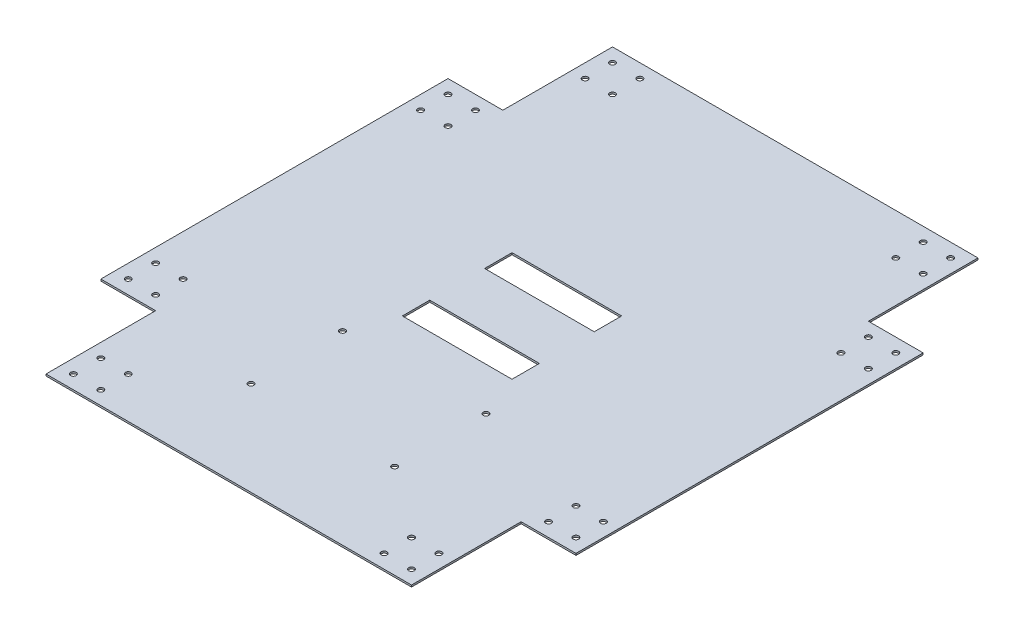
SolidWorks part; units mm, degrees
material "Thornel Mat VMA"
ref_plane "前视基准面" through (0, 0, 0) normal (0, 0, 1) x (1, 0, 0)
ref_plane "上视基准面" through (0, 0, 0) normal (0, 1, 0) x (1, 0, 0)
ref_plane "右视基准面" through (0, 0, 0) normal (1, 0, 0) x (0, 0, -1)
other "Configuration Table"
sketch "草图1" plane through (0, 0, 0) normal (0, 1, 0) x (1, 0, 0)
  line L0 (-154.7477, 33.3852) -> (-154.7477, 153.3852)
  line L1 (-154.7477, 153.3852) -> (245.2523, 153.3852)
  line L2 (245.2523, 153.3852) -> (245.2523, 33.3852)
  line L3 (245.2523, 33.3852) -> (305.2523, 33.3852)
  line L4 (305.2523, 33.3852) -> (305.2523, -346.6148)
  line L5 (305.2523, -346.6148) -> (245.2523, -346.6148)
  line L6 (245.2523, -346.6148) -> (245.2523, -466.6148)
  line L7 (245.2523, -466.6148) -> (-154.7477, -466.6148)
  line L8 (-154.7477, -466.6148) -> (-154.7477, -346.6148)
  line L9 (-154.7477, -346.6148) -> (-214.7477, -346.6148)
  line L10 (-214.7477, -346.6148) -> (-214.7477, 33.3852)
  line L11 (-214.7477, 33.3852) -> (-154.7477, 33.3852)
  line L12 (305.2523, -126.6148) -> (-214.7477, -126.6148)
  line L13 (-214.7477, -186.6148) -> (305.2523, -186.6148)
  line L14 (45.2523, -240.6148) -> (45.2523, -386.6148) construction
  line L15 (-38.2477, -240.6148) -> (128.7523, -240.6148)
  line L16 (-38.2477, -240.6148) -> (-38.2477, -386.6148)
  line L17 (-38.2477, -386.6148) -> (128.7523, -386.6148)
  line L18 (128.7523, -240.6148) -> (128.7523, -386.6148)
  line L19 (45.2523, 153.3852) -> (45.2523, -466.6148) construction
  line L20 (305.2523, -156.6148) -> (-214.7477, -156.6148) construction
  line L22 (-14.7477, -96.6148) -> (105.2523, -96.6148)
  line L23 (-14.7477, -96.6148) -> (-14.7477, -126.6148)
  line L25 (105.2523, -96.6148) -> (105.2523, -126.6148)
  line L30 (105.2523, -216.6148) -> (105.2523, -186.6148)
  line L31 (-14.7477, -216.6148) -> (105.2523, -216.6148)
  line L32 (-14.7477, -216.6148) -> (-14.7477, -186.6148)
  circle A0 centre (-33.2477, -263.6148) radius 3.1
  circle A1 centre (-33.2477, -363.6148) radius 3.1
  circle A2 centre (123.7523, -263.6148) radius 3.1
  circle A3 centre (123.7523, -363.6148) radius 3.1
  circle A4 centre (-139.7477, -421.6148) radius 3.1
  circle A5 centre (-109.7477, -421.6148) radius 3.1
  circle A8 centre (-139.7477, -451.6148) radius 3.1
  circle A9 centre (-109.7477, -451.6148) radius 3.1
  circle A10 centre (230.2523, -451.6148) radius 3.1
  circle A11 centre (200.2523, -451.6148) radius 3.1
  circle A12 centre (200.2523, -421.6148) radius 3.1
  circle A13 centre (230.2523, -421.6148) radius 3.1
  circle A14 centre (200.2523, 138.3852) radius 3.1
  circle A15 centre (230.2523, 138.3852) radius 3.1
  circle A16 centre (230.2523, 108.3852) radius 3.1
  circle A17 centre (200.2523, 108.3852) radius 3.1
  circle A18 centre (-139.7477, 138.3852) radius 3.1
  circle A19 centre (-139.7477, 108.3852) radius 3.1
  circle A20 centre (-109.7477, 108.3852) radius 3.1
  circle A21 centre (-109.7477, 138.3852) radius 3.1
  circle A22 centre (-199.7477, -301.6148) radius 3.1
  circle A23 centre (-169.7477, -301.6148) radius 3.1
  circle A24 centre (-199.7477, -331.6148) radius 3.1
  circle A25 centre (-169.7477, -331.6148) radius 3.1
  circle A26 centre (290.2523, -331.6148) radius 3.1
  circle A27 centre (260.2523, -331.6148) radius 3.1
  circle A28 centre (260.2523, -301.6148) radius 3.1
  circle A29 centre (290.2523, -301.6148) radius 3.1
  circle A30 centre (260.2523, 18.3852) radius 3.1
  circle A31 centre (290.2523, 18.3852) radius 3.1
  circle A32 centre (290.2523, -11.6148) radius 3.1
  circle A33 centre (260.2523, -11.6148) radius 3.1
  circle A34 centre (-199.7477, 18.3852) radius 3.1
  circle A35 centre (-169.7477, 18.3852) radius 3.1
  circle A36 centre (-169.7477, -11.6148) radius 3.1
  circle A37 centre (-199.7477, -11.6148) radius 3.1
  dimension "D11" = 6.2
  dimension "D12" = 6.2
  dimension "D13" = 6.2
  dimension "D1" = 400
  dimension "D2" = 380
  dimension "D3" = 60
  dimension "D4" = 60
  dimension "D5" = 80
  dimension "D6" = 167
  dimension "D7" = 146
  dimension "D8" = 5
  dimension "D9" = 23
  dimension "D10" = 23
  dimension "D14" = 15
  dimension "D15" = 30
  dimension "D16" = 30
  dimension "D17" = 15
  dimension "D18" = 120
  dimension "D19" = 30
  dimension "D20" = 15
  dimension "D21" = 30
  dimension "D22" = 15
  dimension "D23" = 30
  dimension "D24" = 120
  dimension "D25" = 30
  dimension "D26" = 60
extrude "凸台-拉伸1" add sketch "草图1" along normal blind 2
